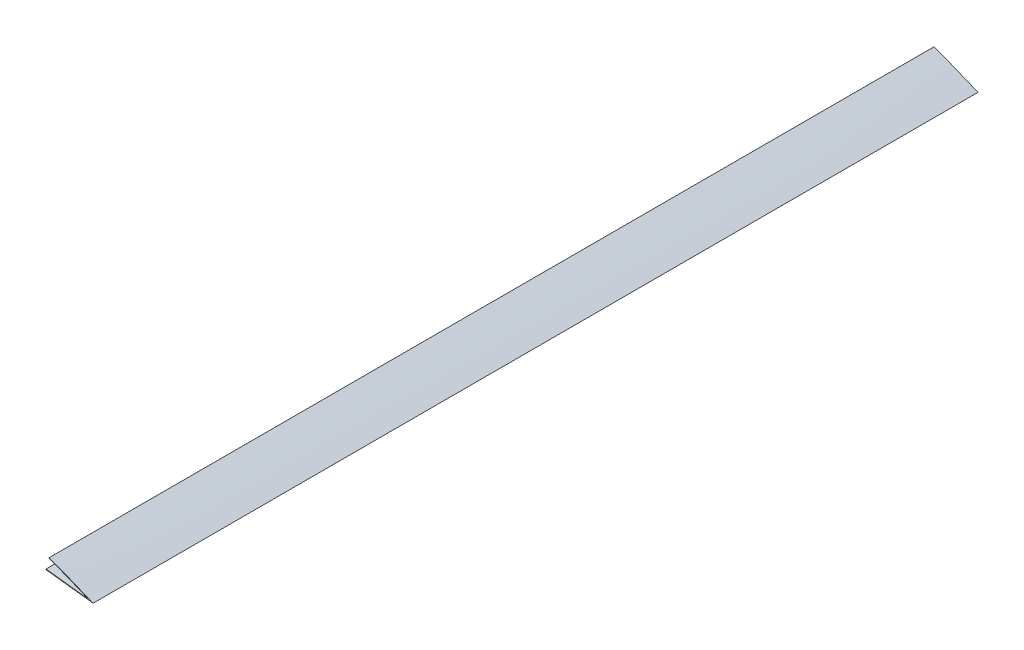
SolidWorks part; units mm, degrees
ref_plane "Front Plane" through (0, 0, 0) normal (0, 0, 1) x (1, 0, 0)
ref_plane "Top Plane" through (0, 0, 0) normal (0, 1, 0) x (1, 0, 0)
ref_plane "Right Plane" through (0, 0, 0) normal (1, 0, 0) x (0, 0, -1)
curve "ImportedCurve1"
curve "ImportedCurve2"
curve "ImportedCurve3"
curve "ImportedCurve4"
curve "ImportedCurve5"
curve "ImportedCurve6"
sketch "Sketch2" plane through (0, 0, 0) normal (0, 0, 1) x (1, 0, 0)
  line L0 (1990.4215, 2953.4976) -> (1990.598, 2953.971) construction
  line L1 (1988.0746, 2944.7099) -> (1988.0231, 2944.186) construction
  line L2 (1990.4215, 2953.4976) -> (1990.598, 2953.971)
  line L3 (1988.0746, 2944.7099) -> (1988.0231, 2944.186)
  spline S0 degree 3 poles (2050.94, 4941.2664) (1888.685, 2927.8357) (1941.6856, 2949.6925) (1992.8786, 2943.6519) (1996.2606, 2943.2782) (1999.5028, 2942.8814) (2002.5951, 2942.5882) (2005.5143, 2942.1987) (2008.2863, 2941.9286) (2010.8855, 2941.5691) (2013.3339, 2941.2998) (2015.6079, 2941.0333) (2017.7058, 2940.7551) (2019.6294, 2940.5785) (2021.3677, 2940.3148) (2022.9312, 2940.1475) (2024.3197, 2939.9779) (2038.9301, 2937.8066) (2055.5575, 2955.2437) (1803.6377, 952.4628) knots 22.673149 22.673149 22.673149 22.673149 28.487933 28.626756 28.761203 28.889816 29.012534 29.128022 29.237609 29.341434 29.437893 29.528519 29.611854 29.687831 29.75659 29.819438 29.873537 29.921805 31.563634 31.563634 31.563634 31.563634 only from (1988.0231, 2944.186) to (2026.3781, 2939.726) construction
  spline S1 degree 3 poles (867.7677, 1313.6067) (2167.7538, 2910.2729) (2087.3249, 2915.176) (2024.5633, 2940.4512) (2024.2524, 2940.5764) (2023.9421, 2940.702) (2023.6323, 2940.8284) (2019.9229, 2942.3416) (2016.3, 2943.9544) (2008.8404, 2946.8849) (2005.182, 2948.446) (1998.4983, 2950.9926) (1995.5753, 2952.1437) (1920.7825, 2979.4741) (1866.1971, 3038.6633) (1027.5915, 1206.0569) knots -7.782935 -7.782935 -7.782935 -7.782935 0.175577 0.175577 0.175577 0.214991 0.214991 0.214991 0.686933 0.686933 1.158874 1.158874 1.531655 1.531655 10.550851 10.550851 10.550851 10.550851 only from (2026.3781, 2939.726) to (1990.598, 2953.971) construction
  spline S2 degree 3 poles (23.4108, 2968.9614) (2138.3323, 2898.6666) (2065.778, 2922.8165) (2015.2173, 2943.7878) (2010.8021, 2945.5756) (2001.8663, 2949.1968) (1997.4462, 2950.8924) (1868.7827, 2998.6016) (1749.4483, 3050.1497) (694.8477, 1446.3032) knots -5.519211 -5.519211 -5.519211 -5.519211 0.376825 0.376825 0.943228 0.943228 1.509632 1.509632 17.170956 17.170956 17.170956 17.170956 only from (2022.8665, 2940.6146) to (1990.4215, 2953.4976) construction
  spline S3 degree 3 poles (866.9002, 4566.3608) (1577.8734, 2902.182) (1784.4722, 2968.0253) (1998.0522, 2943.5758) (2004.5957, 2942.8668) (2100.0462, 2931.1201) (2169.3996, 2901.7231) (3686.1248, 4046.4063) knots 3.975353 3.975353 3.975353 3.975353 28.56999 28.56999 29.343341 29.343341 39.990926 39.990926 39.990926 39.990926 only from (1988.0746, 2944.7099) to (2022.8665, 2940.6146) construction
  spline S4 degree 3 poles (1988.0231, 2944.186) (1988.4861, 2944.1404) (1990.1186, 2943.9776) (1992.8786, 2943.6519) (1996.2606, 2943.2782) (1999.5028, 2942.8814) (2002.5951, 2942.5882) (2005.5143, 2942.1987) (2008.2863, 2941.9286) (2010.8855, 2941.5691) (2013.3339, 2941.2998) (2015.6079, 2941.0333) (2017.7058, 2940.7551) (2019.6294, 2940.5785) (2021.3677, 2940.3148) (2022.9312, 2940.1475) (2024.3197, 2939.9779) (2025.4405, 2939.8113) (2026.1137, 2939.7556) (2026.3781, 2939.726) knots 28.432981 28.432981 28.432981 28.432981 28.487933 28.626756 28.761203 28.889816 29.012534 29.128022 29.237609 29.341434 29.437893 29.528519 29.611854 29.687831 29.75659 29.819438 29.873537 29.921805 29.95324 29.95324 29.95324 29.95324
  spline S5 degree 3 poles (2026.3781, 2939.726) (2025.7724, 2939.9668) (2025.167, 2940.2081) (2024.5633, 2940.4512) (2024.2524, 2940.5764) (2023.9421, 2940.702) (2023.6323, 2940.8284) (2019.9229, 2942.3416) (2016.3, 2943.9544) (2008.8404, 2946.8849) (2005.182, 2948.446) (1998.4983, 2950.9926) (1995.5753, 2952.1437) (1991.9359, 2953.4736) (1991.2665, 2953.7216) (1990.598, 2953.971) knots 0.099021 0.099021 0.099021 0.099021 0.175577 0.175577 0.175577 0.214991 0.214991 0.214991 0.686933 0.686933 1.158874 1.158874 1.531655 1.531655 1.615896 1.615896 1.615896 1.615896
  spline S6 degree 3 poles (2022.8665, 2940.6146) (2021.798, 2941.0615) (2020.7163, 2941.507) (2015.2173, 2943.7878) (2010.8021, 2945.5756) (2001.8663, 2949.1968) (1997.4462, 2950.8924) (1992.1106, 2952.8708) (1991.2661, 2953.1843) (1990.4215, 2953.4976) knots 0.240373 0.240373 0.240373 0.240373 0.376825 0.376825 0.943228 0.943228 1.509632 1.509632 1.616177 1.616177 1.616177 1.616177
  spline S7 degree 3 poles (1988.0746, 2944.7099) (1989.2302, 2944.5829) (1990.3856, 2944.4534) (1998.0522, 2943.5758) (2004.5957, 2942.8668) (2014.9909, 2941.5875) (2018.8846, 2941.0676) (2022.8665, 2940.6146) knots 28.432747 28.432747 28.432747 28.432747 28.56999 28.56999 29.343341 29.343341 29.813814 29.813814 29.813814 29.813814
extrude "Boss-Extrude1" add sketch "Sketch2" along normal blind 720.725
